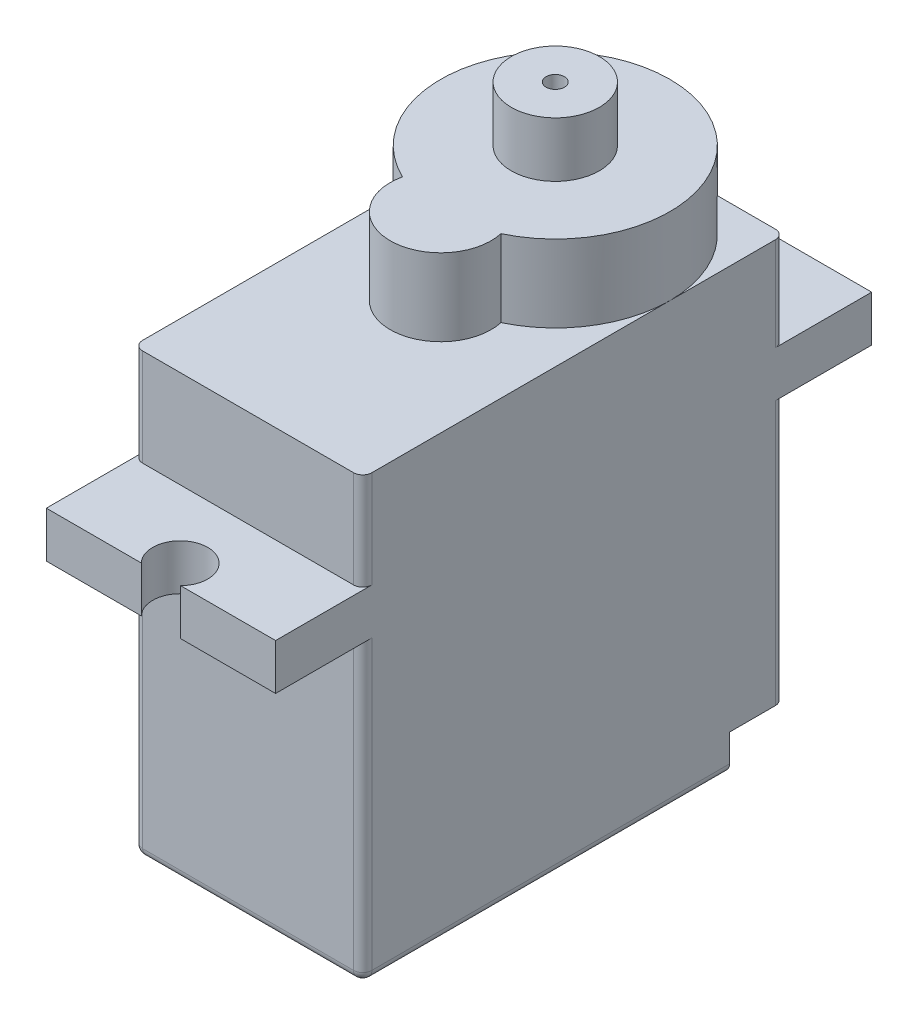
SolidWorks part; units mm, degrees
ref_plane "Front Plane" through (0, 0, 0) normal (0, 0, 1) x (1, 0, 0)
ref_plane "Top Plane" through (0, 0, 0) normal (0, 1, 0) x (1, 0, 0)
ref_plane "Right Plane" through (0, 0, 0) normal (1, 0, 0) x (0, 0, -1)
sketch "Sketch1" plane through (0, 0, 0) normal (0, 1, 0) x (1, 0, 0)
  line L0 (-6.25, 11.5) -> (6.25, -11.5) construction
  line L1 (-6.25, 11.5) -> (6.25, 11.5)
  line L2 (-6.25, 11.5) -> (-6.25, -11.5)
  line L3 (-6.25, -11.5) -> (6.25, -11.5)
  line L4 (6.25, 11.5) -> (6.25, -11.5)
  line L5 (6.25, 11.5) -> (-6.25, -11.5) construction
  point P7 (0, 0)
  dimension "D1" = 23
  dimension "D2" = 12.5
extrude "Boss-Extrude1" add sketch "Sketch1" along normal blind 24
sketch "Sketch2" plane through (0, 24, 0) normal (0, 1, 0) x (1, 0, 0)
  line L0 (6.25, -11.5) -> (6.25, 11.5) construction
  line L1 (6.25, 11.5) -> (-6.25, 11.5) construction
  line L2 (-6.25, 11.5) -> (-6.25, -11.5) construction
  line L3 (6.25, -11.5) -> (6.25, 11.5) construction
  line L4 (6.25, 11.5) -> (-6.25, 11.5) construction
  line L5 (-6.25, 11.5) -> (-6.25, -11.5) construction
  arc A0 (2.6826, -0.395) -> (-2.6826, -0.395) centre (0, 5.25) ccw
  arc A1 (-2.6826, -0.395) -> (2.6826, -0.395) centre (0, -1) ccw
  dimension "D1" = 5.5
extrude "Boss-Extrude2" add sketch "Sketch2" along normal blind 4.2 contours A0 A1
sketch "Sketch3" plane through (0, 28.2, 0) normal (0, 1, 0) x (1, 0, 0)
  arc A0 (2.6826, -0.395) -> (-2.6826, -0.395) centre (0, 5.25) ccw construction
  arc A1 (2.6826, -0.395) -> (-2.6826, -0.395) centre (0, 5.25) ccw construction
  circle A2 centre (0, 5.25) radius 2.4
  circle A3 centre (0, 5.25) radius 0.5
  dimension "D1" = 4.8
  dimension "D2" = 1
extrude "Boss-Extrude3" add sketch "Sketch3" along normal blind 3
sketch "Sketch4" plane through (0, 0, -11.5) normal (0, 0, -1) x (-1, 0, 0)
  line L0 (6.25, 24) -> (6.25, 0) construction
  line L1 (-6.25, 24) -> (-6.25, 0) construction
  line L2 (6.25, 24) -> (6.25, 0) construction
  line L3 (-6.25, 24) -> (-6.25, 0) construction
  line L5 (-6.25, 18.9) -> (6.25, 18.9)
  line L6 (-6.25, 18.9) -> (-6.25, 16.4)
  line L7 (-6.25, 16.4) -> (6.25, 16.4)
  line L8 (6.25, 18.9) -> (6.25, 16.4)
  dimension "D1" = 16.4
  dimension "D2" = 2.5
extrude "Boss-Extrude4" add sketch "Sketch4" along normal blind 4.75
sketch "Sketch5" plane through (0, 0, 11.5) normal (0, 0, 1) x (1, 0, 0)
  line L0 (-6.25, 24) -> (-6.25, 0) construction
  line L1 (6.25, 24) -> (6.25, 0) construction
  line L2 (-6.25, 24) -> (-6.25, 0) construction
  line L3 (6.25, 24) -> (6.25, 0) construction
  line L5 (6.25, 16.2) -> (-6.25, 16.2)
  line L6 (6.25, 16.2) -> (6.25, 18.7)
  line L7 (6.25, 18.7) -> (-6.25, 18.7)
  line L8 (-6.25, 16.2) -> (-6.25, 18.7)
  dimension "D1" = 16.2
  dimension "D2" = 2.5
extrude "Boss-Extrude5" add sketch "Sketch5" along normal blind 4.75
sketch "Sketch6" plane through (0, 18.7, 0) normal (0, 1, 0) x (1, 0, 0)
  line L0 (0, -16.25) -> (0, -11.5) construction
  line L10 (6.25, -11.5) -> (-6.25, -11.5) construction
  line L11 (6.25, -16.25) -> (6.25, -11.5) construction
  line L12 (-6.25, -16.25) -> (-6.25, -11.5) construction
  line L13 (6.25, -16.25) -> (-6.25, -16.25) construction
  line L14 (6.25, -11.5) -> (-6.25, -11.5) construction
  line L15 (6.25, -16.25) -> (6.25, -11.5) construction
  line L16 (-6.25, -16.25) -> (-6.25, -11.5) construction
  line L17 (6.25, -16.25) -> (-6.25, -16.25) construction
  circle A0 centre (0, -15.2) radius 1.5
  dimension "D1" = 3
  dimension "D2" = 3.7
extrude "Cut-Extrude1" cut sketch "Sketch6" against normal up to next
sketch "Sketch8" plane through (0, 18.9, 0) normal (0, 1, 0) x (1, 0, 0)
  line L0 (-6.25, 16.25) -> (6.25, 16.25) construction
  line L1 (-6.25, 16.25) -> (-6.25, 11.5) construction
  line L2 (-6.25, 11.5) -> (6.25, 11.5) construction
  line L3 (6.25, 16.25) -> (6.25, 11.5) construction
  line L4 (-6.25, 16.25) -> (6.25, 16.25) construction
  line L5 (-6.25, 16.25) -> (-6.25, 11.5) construction
  line L6 (-6.25, 11.5) -> (6.25, 11.5) construction
  line L7 (6.25, 16.25) -> (6.25, 11.5) construction
  line L8 (0, 16.25) -> (0, 11.5) construction
  circle A0 centre (0, 15.2) radius 1.5
  dimension "D1" = 3
  dimension "D2" = 3.7
extrude "Cut-Extrude2" cut sketch "Sketch8" against normal up to next contours A0
sketch "Sketch9" plane through (6.25, 0, 0) normal (1, 0, 0) x (0, 0, -1)
  line L0 (11.5, 2) -> (8.5, 0)
  line L1 (11.5, 16.4) -> (11.5, 0) construction
  line L2 (-11.5, 0) -> (11.5, 0) construction
  line L3 (8.5, 0) -> (11.5, 0)
  line L4 (11.5, 0) -> (11.5, 2)
  line L5 (11.5, 2) -> (8.5, 2) construction
  line L6 (8.5, 2) -> (8.5, 0) construction
  dimension "D1" = 2
  dimension "3" = 3
extrude "Cut-Extrude4" cut sketch "Sketch9" against normal through all contours L0 L3 L4
sketch "Sketch10" plane through (6.25, 0, 0) normal (1, 0, 0) x (0, 0, -1)
  line L0 (11.5, 2) -> (8.5, 2)
  line L1 (8.5, 0) -> (8.5, 2)
  dimension "D1" = 3
extrude "Cut-Extrude6" cut sketch "Sketch10" against normal blind 2.3 and the other way through all flip side to cut
sketch "Sketch11" plane through (-6.25, 0, 0) normal (-1, 0, 0) x (0, 0, 1)
  line L0 (-11.5, 2) -> (-8.5, 2)
  line L1 (-8.5, 2) -> (-8.5, 0)
extrude "Cut-Extrude7" cut sketch "Sketch11" against normal blind 2.3 and the other way through all flip side to cut
fillet "Fillet1" radius 0.5 11 edges at (-6.25, 21.45, -11.5) (6.25, 21.45, -11.5) (-6.25, 21.35, 11.5) (0, 0, 11.5) (6.25, 0, 1.5) (-6.25, 0, 1.5) (6.25, 9.2, -11.5) (-6.25, 9.2, -11.5) (-6.25, 8.1, 11.5) (6.25, 8.1, 11.5) (6.25, 21.35, 11.5)
